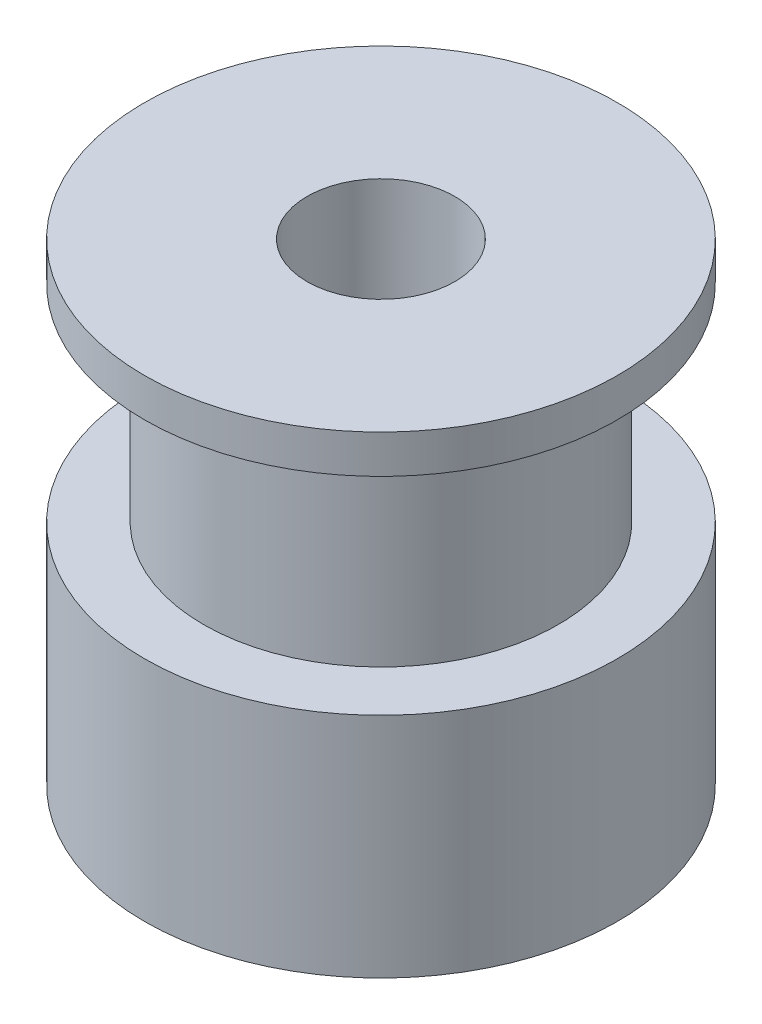
SolidWorks part; units mm, degrees
material "Plain Carbon Steel"
ref_plane "Front Plane" through (0, 0, 0) normal (0, 0, 1) x (1, 0, 0)
ref_plane "Top Plane" through (0, 0, 0) normal (0, 1, 0) x (1, 0, 0)
ref_plane "Right Plane" through (0, 0, 0) normal (1, 0, 0) x (0, 0, -1)
sketch "Sketch1" plane through (0, 0, 0) normal (0, 1, 0) x (1, 0, 0)
  circle A0 centre (0, 0) radius 8
  circle A1 centre (0, 0) radius 2.5
  dimension "D1" = 16
  dimension "D2" = 5
extrude "Boss-Extrude1" add sketch "Sketch1" along normal blind 16
sketch "Sketch2" plane through (0, 0, 0) normal (0, 0, 1) x (1, 0, 0)
  line L0 (-8, 16) -> (-8, 0) construction
  line L1 (-8, 14.7) -> (-6, 14.7)
  line L2 (-8, 14.7) -> (-8, 7.7)
  line L3 (-8, 7.7) -> (-6, 7.7)
  line L4 (-6, 14.7) -> (-6, 7.7)
  line L5 (8, 16) -> (-8, 16) construction
  line L6 (0, 16.9384) -> (0, -0.7305) construction
  dimension "D1" = 1.3
  dimension "D2" = 2
  dimension "D3" = 7
revolve "Cut-Revolve1" cut sketch "Sketch2" angle 360 about L6
ref_plane "Plane1" through (-8, 0, 0) normal (-1, 0, 0) x (0, 0, 1)
sketch "Sketch3" plane through (-8, 0, 0) normal (-1, 0, 0) x (0, 0, 1)
  line L0 (8, 7.7) -> (-8, 7.7) construction
  circle A0 centre (0, 3.7) radius 1.55
  point P2 (0, 0)
  dimension "D1" = 3.1
  dimension "D2" = 4
extrude "Cut-Extrude1" cut sketch "Sketch3" against normal blind 8
pattern_circular "CirPattern1" count 2 every 90 about axis through (0, 16, 0) along (0, -1, 0) of "Cut-Extrude1"
